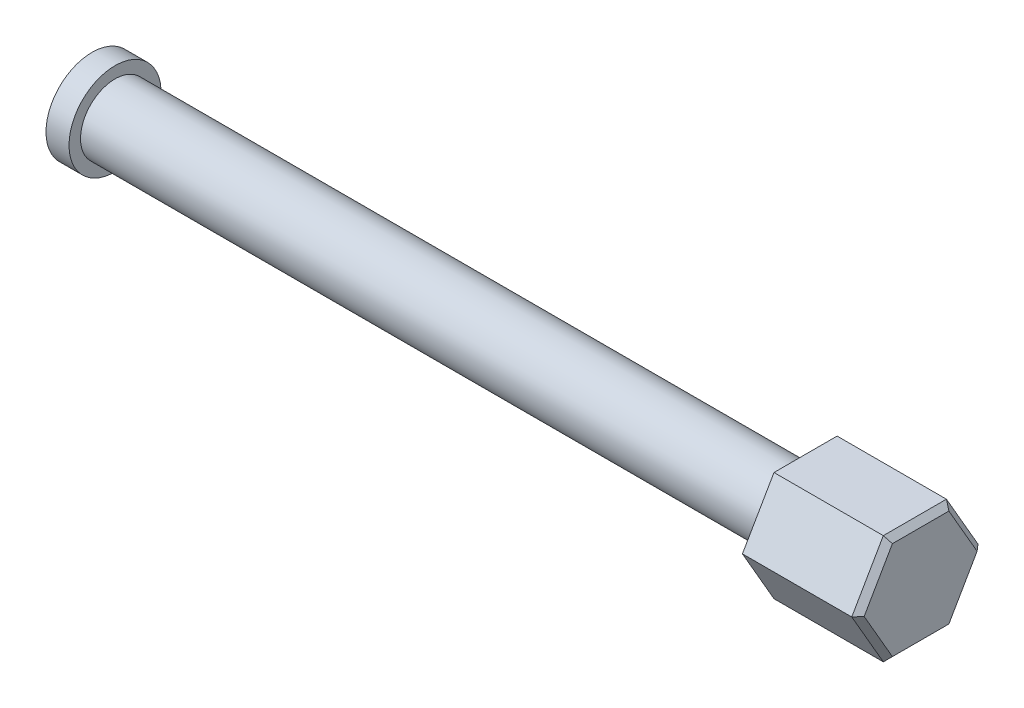
SolidWorks part; units mm, degrees
material "Инструментальная сталь типа AISI A2"
ref_plane "Спереди" through (0, 0, 0) normal (0, 0, 1) x (1, 0, 0)
ref_plane "Сверху" through (0, 0, 0) normal (0, 1, 0) x (1, 0, 0)
ref_plane "Справа" through (0, 0, 0) normal (1, 0, 0) x (0, 0, -1)
sketch "Эскиз1" plane through (0, 0, 0) normal (0, 1, 0) x (1, 0, 0)
  line L0 (-81.5752, 0) -> (-64.6451, 0) construction
  line L1 (-64.6451, 0) -> (-64.6451, 8)
  line L2 (-64.6451, 8) -> (-60.6451, 8)
  line L3 (-60.6451, 8) -> (-60.6451, 6)
  line L4 (-60.6451, 6) -> (59.3549, 6)
  line L5 (79.3549, 0) -> (-64.6451, 0)
  line L9 (59.3549, 6) -> (59.3549, 11)
  line L10 (59.3549, 11) -> (79.3549, 11)
  line L11 (79.3549, 11) -> (79.3549, 0)
  dimension "D1" = 8
  dimension "D2" = 120
  dimension "D3" = 6
  dimension "D5" = 11
  dimension "D7" = 20
  dimension "D10" = 4
revolve "Повернуть1" add sketch "Эскиз1" angle 360 about L0
cosmetic thread "Условное изображение резьбы1" parameters "D2"=10.072
sketch "Эскиз2" plane through (79.3549, 0, 0) normal (1, 0, 0) x (0, 0, -1)
  line L1 (10.9697, 0) -> (5.4848, 9.5)
  line L2 (5.4848, 9.5) -> (-5.4848, 9.5)
  line L3 (-5.4848, 9.5) -> (-10.9697, 0)
  line L4 (-10.9697, 0) -> (-5.4848, -9.5)
  line L5 (-5.4848, -9.5) -> (5.4848, -9.5)
  line L6 (5.4848, -9.5) -> (10.9697, 0)
  circle A0 centre (0, 0) radius 9.5 construction
extrude "Вырез-Вытянуть1" cut sketch "Эскиз2" against normal blind 20 flip side to cut
chamfer "Фаска1" distance 1 angle 45 6 edges at (79.3549, -9.5, 0) (79.3549, -4.75, 8.2272) (79.3549, 4.75, 8.2272) (79.3549, 9.5, 0) (79.3549, 4.75, -8.2272) (79.3549, -4.75, -8.2272)
sketch "Эскиз3" plane through (-64.6451, 0, 0) normal (-1, 0, 0) x (0, 0, 1)
  circle A0 centre (0, 0) radius 3
  dimension "D1" = 6
extrude "Вырез-Вытянуть2" cut sketch "Эскиз3" against normal blind 3 draft 40
